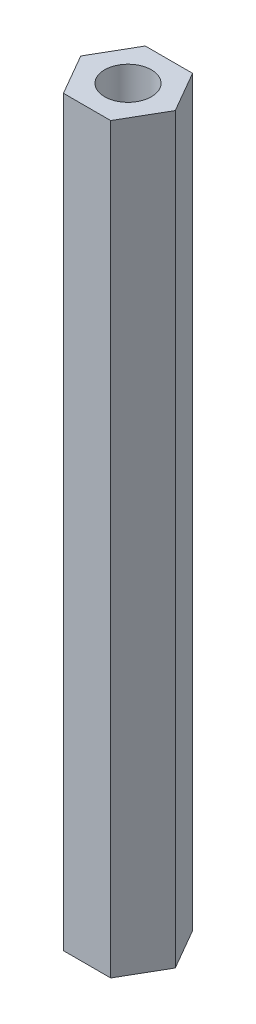
SolidWorks part; units mm, degrees
ref_plane "Front Plane" through (0, 0, 0) normal (0, 0, 1) x (1, 0, 0)
ref_plane "Top Plane" through (0, 0, 0) normal (0, 1, 0) x (1, 0, 0)
ref_plane "Right Plane" through (0, 0, 0) normal (1, 0, 0) x (0, 0, -1)
sketch "Sketch1" plane through (0, 0, 0) normal (0, 1, 0) x (1, 0, 0)
  line L1 (-2.0207, 3.5) -> (-4.0415, 0)
  line L2 (-4.0415, 0) -> (-2.0207, -3.5)
  line L3 (-2.0207, -3.5) -> (2.0207, -3.5)
  line L4 (2.0207, -3.5) -> (4.0415, 0)
  line L5 (4.0415, 0) -> (2.0207, 3.5)
  line L6 (2.0207, 3.5) -> (-2.0207, 3.5)
  circle A0 centre (0, 0) radius 3.5 construction
  circle A1 centre (0, 0) radius 2
  dimension "D1" = 4
  dimension "D2" = 7
extrude "Boss-Extrude1" add sketch "Sketch1" along normal blind 63.5
